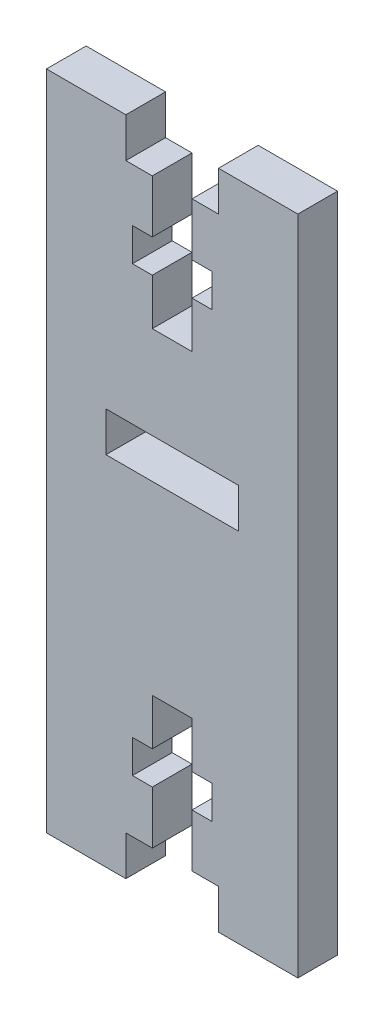
SolidWorks part; units mm, degrees
ref_plane "Plan de face" through (0, 0, 0) normal (0, 0, 1) x (1, 0, 0)
ref_plane "Plan de dessus" through (0, 0, 0) normal (0, 1, 0) x (1, 0, 0)
ref_plane "Plan de droite" through (0, 0, 0) normal (1, 0, 0) x (0, 0, -1)
sketch "Esquisse10" plane through (0, 0, 0) normal (0, 0, 1) x (1, 0, 0)
  line L0 (-4.9857, -60.4764) -> (1.0143, -60.4764)
  line L1 (-17.9857, -110.4764) -> (-11.9857, -110.4764)
  line L2 (-17.9857, -110.4764) -> (-17.9857, -60.4764)
  line L3 (-17.9857, -60.4764) -> (-11.9857, -60.4764)
  line L4 (1.0143, -110.4764) -> (1.0143, -60.4764)
  line L5 (-9.9857, -97.4764) -> (-6.9857, -97.4764)
  line L6 (-9.9857, -97.4764) -> (-9.9857, -100.9764)
  line L7 (-9.9857, -67.4764) -> (-11.4857, -67.4764)
  line L8 (-6.9857, -97.4764) -> (-6.9857, -100.9764)
  line L9 (-9.9857, -73.4764) -> (-6.9857, -73.4764)
  line L10 (-9.9857, -73.4764) -> (-9.9857, -69.9764)
  line L11 (-5.4857, -69.9764) -> (-6.9857, -69.9764)
  line L12 (-6.9857, -73.4764) -> (-6.9857, -69.9764)
  line L13 (-11.9857, -107.4764) -> (-9.9857, -107.4764)
  line L14 (-11.9857, -107.4764) -> (-11.9857, -110.4764)
  line L15 (-9.9857, -69.9764) -> (-11.4857, -69.9764)
  line L16 (-4.9857, -107.4764) -> (-4.9857, -110.4764)
  line L17 (-11.9857, -63.4764) -> (-9.9857, -63.4764)
  line L18 (-11.9857, -63.4764) -> (-11.9857, -60.4764)
  line L19 (-4.9857, -110.4764) -> (1.0143, -110.4764)
  line L20 (-4.9857, -63.4764) -> (-4.9857, -60.4764)
  line L21 (-6.9857, -107.4764) -> (-4.9857, -107.4764)
  line L22 (-6.9857, -63.4764) -> (-4.9857, -63.4764)
  line L23 (-5.4857, -69.9764) -> (-5.4857, -67.4764)
  line L24 (-5.4857, -67.4764) -> (-6.9857, -67.4764)
  line L25 (-11.4857, -69.9764) -> (-11.4857, -67.4764)
  line L26 (-5.4857, -103.4764) -> (-6.9857, -103.4764)
  line L27 (-5.4857, -103.4764) -> (-5.4857, -100.9764)
  line L28 (-5.4857, -100.9764) -> (-6.9857, -100.9764)
  line L29 (-11.4857, -103.4764) -> (-11.4857, -100.9764)
  line L30 (-9.9857, -67.4764) -> (-9.9857, -63.4764)
  line L31 (-6.9857, -67.4764) -> (-6.9857, -63.4764)
  line L32 (-9.9857, -103.4764) -> (-11.4857, -103.4764)
  line L33 (-9.9857, -100.9764) -> (-11.4857, -100.9764)
  line L34 (-9.9857, -103.4764) -> (-9.9857, -107.4764)
  line L35 (-6.9857, -103.4764) -> (-6.9857, -107.4764)
  line L37 (-13.4857, -80.4764) -> (-3.4857, -80.4764)
  line L38 (-13.4857, -80.4764) -> (-13.4857, -83.4764)
  line L39 (-13.4857, -83.4764) -> (-3.4857, -83.4764)
  line L40 (-3.4857, -80.4764) -> (-3.4857, -83.4764)
  dimension "D1" = 19
  dimension "D2" = 50
  dimension "D3" = 3
  dimension "D4" = 3
  dimension "D5" = 8
  dimension "D6" = 8
  dimension "D7" = 2.5
  dimension "D8" = 2.5
  dimension "D9" = 3
  dimension "D10" = 3
  dimension "D11" = 2
  dimension "D12" = 2
  dimension "D13" = 2
  dimension "D14" = 2
  dimension "D15" = 1.5
  dimension "D16" = 1.5
  dimension "D17" = 6
  dimension "D18" = 6
  dimension "D19" = 4
  dimension "D20" = 4
  dimension "D21" = 3
  dimension "D22" = 10
  dimension "D23" = 4.5
  dimension "D24" = 20
  dimension "D25" = 13
  dimension "D26" = 13
extrude "Boss.-Extru.10" add sketch "Esquisse10" along normal blind 3 separate body
